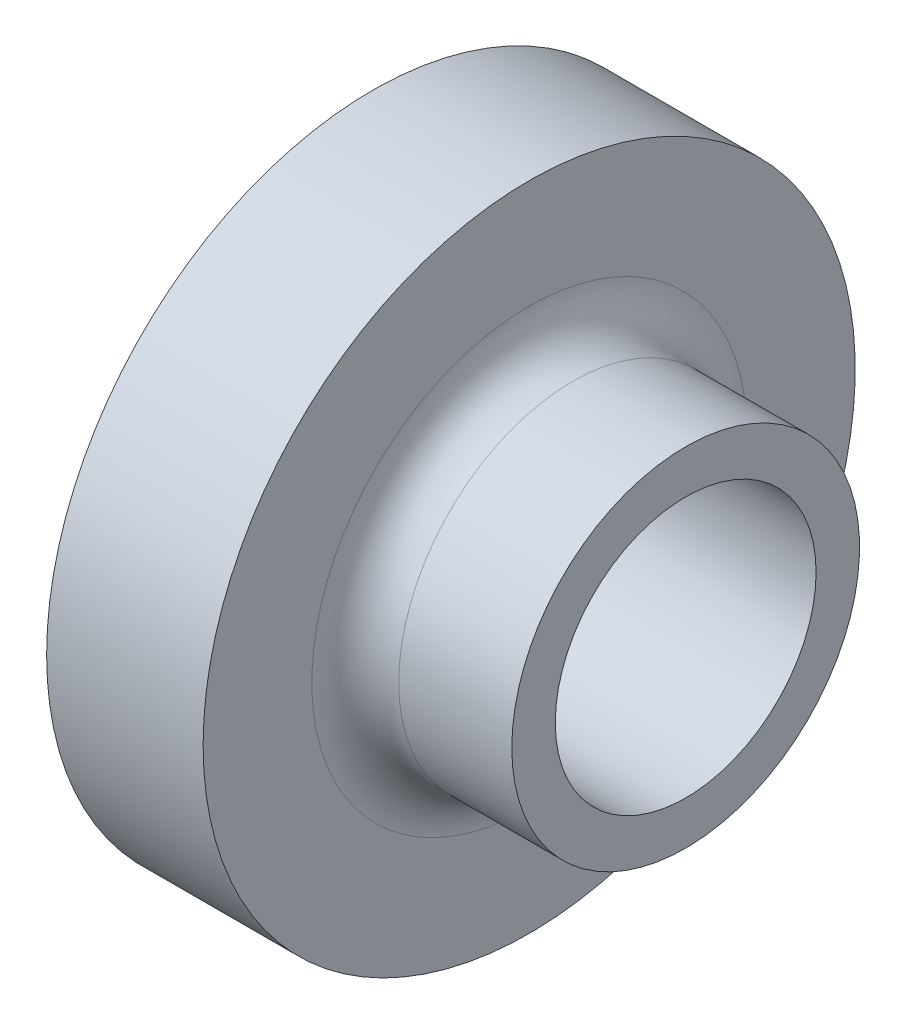
SolidWorks part; units mm, degrees
ref_plane "Ön Düzlem" through (0, 0, 0) normal (0, 0, 1) x (1, 0, 0)
ref_plane "Üst Düzlem" through (0, 0, 0) normal (0, 1, 0) x (1, 0, 0)
ref_plane "Sağ Düzlem" through (0, 0, 0) normal (1, 0, 0) x (0, 0, -1)
sketch "Çizim1" plane through (0, 0, 0) normal (0, 0, 1) x (1, 0, 0)
  line L0 (0, 0) -> (50.8524, 0) construction
  line L1 (0, 14.8791) -> (0, 37.5)
  line L2 (0, 37.5) -> (18, 37.5)
  line L3 (18, 37.5) -> (18, 20)
  line L4 (18, 20) -> (36, 20)
  line L5 (36, 20) -> (36, 15)
  line L6 (36, 15) -> (0, 15)
  line L7 (0, 15) -> (0, 14.8791)
  point P12 (0, 0)
  dimension "D1" = 75
  dimension "D2" = 18
  dimension "D3" = 5
  dimension "D4" = 36
  dimension "D5" = 30
revolve "Döndür1" add sketch "Çizim1" angle 360 about L0
fillet "Radyus1" radius 5 1 edges at (18, 0, 20)
